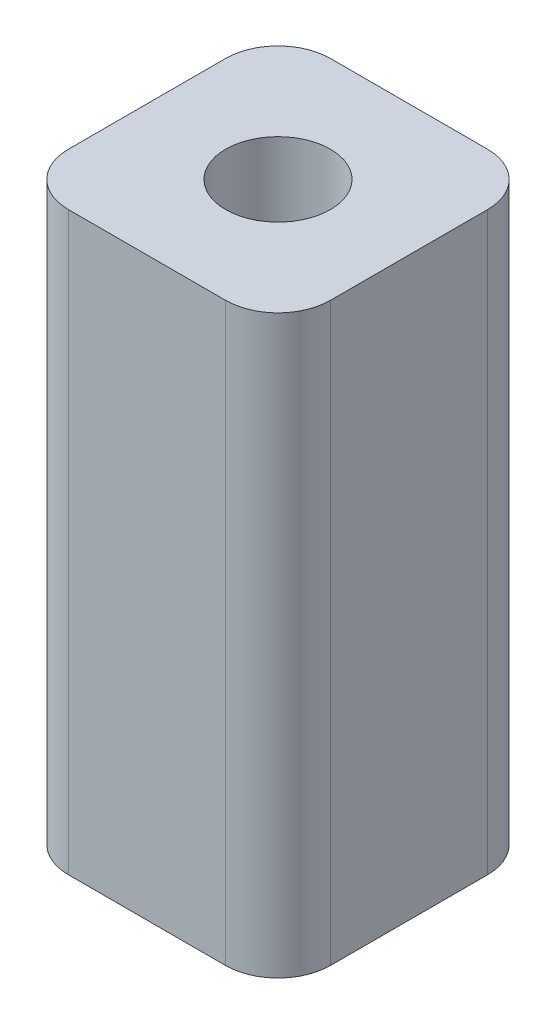
SolidWorks part; units mm, degrees
ref_plane "Спереди" through (0, 0, 0) normal (0, 0, 1) x (1, 0, 0)
ref_plane "Сверху" through (0, 0, 0) normal (0, 1, 0) x (1, 0, 0)
ref_plane "Справа" through (0, 0, 0) normal (1, 0, 0) x (0, 0, -1)
sketch "Эскиз1" plane through (0, 0, 0) normal (0, 1, 0) x (1, 0, 0)
  line L1 (-1.5, 2.5) -> (1.5, 2.5)
  line L2 (-2.5, 1.5) -> (-2.5, -1.5)
  line L3 (-1.5, -2.5) -> (1.5, -2.5)
  line L4 (2.5, 1.5) -> (2.5, -1.5)
  circle A1 centre (0, 0) radius 1
  arc A2 (-2.5, -1.5) -> (-1.5, -2.5) centre (-1.5, -1.5) ccw
  arc A3 (1.5, -2.5) -> (2.5, -1.5) centre (1.5, -1.5) ccw
  arc A4 (1.5, 2.5) -> (2.5, 1.5) centre (1.5, 1.5) cw
  arc A5 (-1.5, 2.5) -> (-2.5, 1.5) centre (-1.5, 1.5) ccw
  point P7 (0, 0)
  point P8 (-2.5, 0)
  point P9 (0, 2.5)
  point P12 (-2.5, -2.5)
  point P15 (2.5, -2.5)
  dimension "D1" = 5
  dimension "D2" = 2
  dimension "D3" = 1
extrude "Бобышка-Вытянуть1" add sketch "Эскиз1" along normal blind 11
